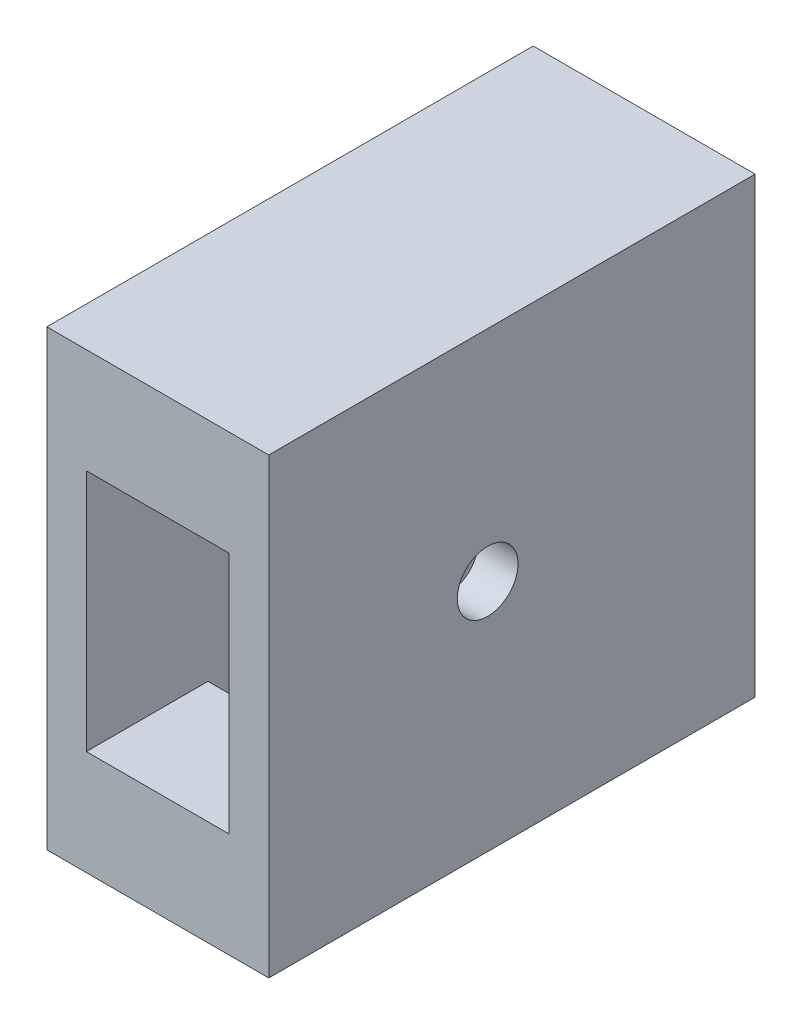
SolidWorks part; units mm, degrees
ref_plane "Front Plane" through (0, 0, 0) normal (0, 0, 1) x (1, 0, 0)
ref_plane "Top Plane" through (0, 0, 0) normal (0, 1, 0) x (1, 0, 0)
ref_plane "Right Plane" through (0, 0, 0) normal (1, 0, 0) x (0, 0, -1)
sketch "Sketch1" plane through (0, 0, 0) normal (0, 0, 1) x (1, 0, 0)
  line L0 (-1.3, 13.6) -> (6, 13.6)
  line L1 (0, 0) -> (4.7, 0)
  line L2 (0, 0) -> (0, 12.3)
  line L3 (0, 12.3) -> (4.7, 12.3)
  line L4 (4.7, 0) -> (4.7, 12.3)
  line L5 (6, -1.3) -> (6, 13.6)
  line L6 (-1.3, -1.3) -> (6, -1.3)
  line L7 (-1.3, -1.3) -> (-1.3, 13.6)
  dimension "D1" = 4.7
  dimension "D2" = 12.3
  dimension "D3" = 1.3
extrude "Boss-Extrude1" add sketch "Sketch1" along normal blind 16
sketch "Sketch4" plane through (0, 0, 0) normal (0, 0, 1) x (1, 0, 0)
  line L0 (0, 6.15) -> (4.7, 6.15) construction
  line L1 (0, 12.3) -> (0, 0) construction
  line L2 (4.7, 0) -> (4.7, 12.3) construction
  line L3 (0, 2.15) -> (4.7, 2.15)
  line L4 (0, 12.3) -> (4.7, 12.3)
  line L5 (0, 12.3) -> (0, 10.15)
  line L6 (0, 10.15) -> (4.7, 10.15)
  line L7 (4.7, 12.3) -> (4.7, 10.15)
  line L8 (4.7, 0) -> (4.7, 2.15)
  line L9 (0, 0) -> (4.7, 0)
  line L10 (0, 0) -> (0, 2.15)
  dimension "D1" = 4
extrude "Boss-Extrude2" add sketch "Sketch4" along normal up to surface (4 mm away) from offset 12 up to face at (2.35, 6.15, 16)
sketch "Sketch5" plane through (-1.3, 0, 0) normal (-1, 0, 0) x (0, 0, 1)
  line L0 (16, 13.6) -> (0, 13.6) construction
  line L1 (0, 13.6) -> (0, -1.3) construction
  circle A0 centre (8.8, 6.4) radius 1
  dimension "D2" = 8.8
  dimension "D3" = 2
  dimension "D1" = 7.2
extrude "Cut-Extrude1" cut sketch "Sketch5" against normal blind 15
